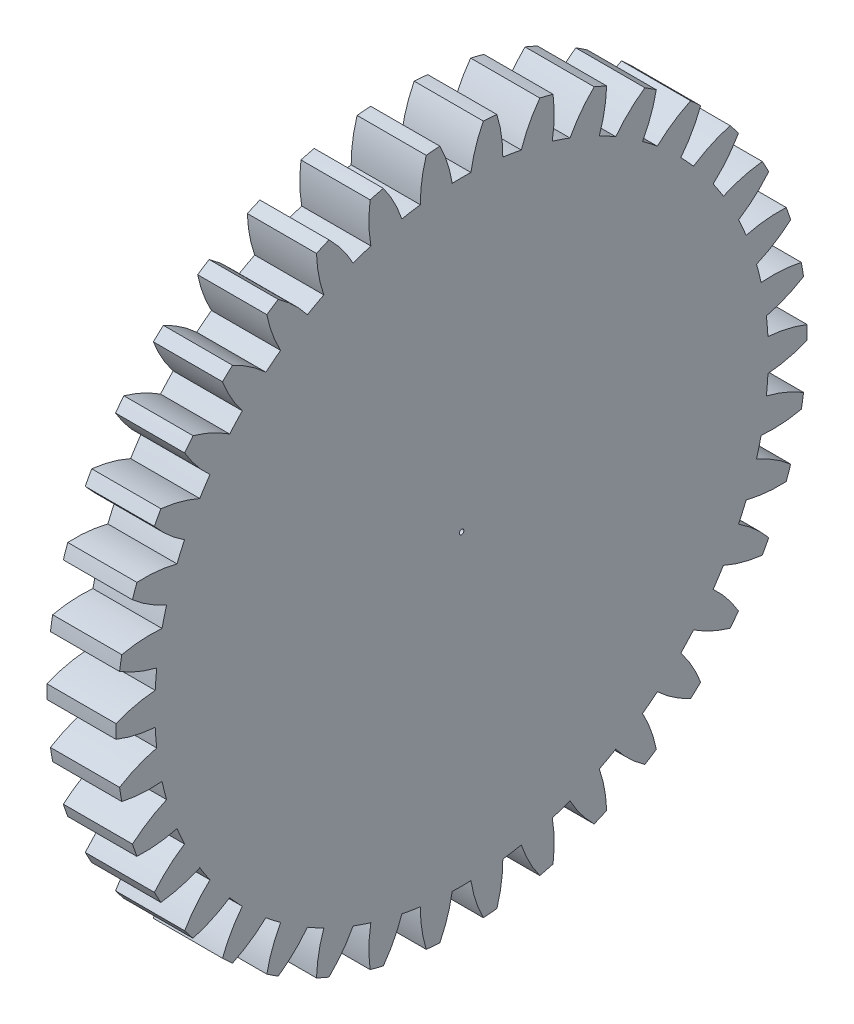
SolidWorks part; units mm, degrees
ref_plane "Plane1" through (0, 0, 0) normal (0, 0, 1) x (1, 0, 0)
ref_plane "Plane2" through (0, 0, 0) normal (0, 1, 0) x (1, 0, 0)
ref_plane "Plane3" through (0, 0, 0) normal (1, 0, 0) x (0, 0, -1)
sketch "HoldingSke" plane through (0, 0, 0) normal (0, 1, 0) x (1, 0, 0)
  line L0 (0, 0) -> (0.2627, -0.2052)
  line L1 (-15, 0) -> (100, 0) construction
  line L2 (0, 0) -> (-2.1039, 2.3779)
  line L3 (0, 0) -> (-11.863, 4.5341)
  line L4 (0, 0) -> (6.8053, 5.3169)
  line L5 (0, 0) -> (-46.8476, -17.4728)
  line L6 (0, 0) -> (-9.9476, -6.7116)
  line L7 (-2.1039, 2.3779) -> (8.6586, 51.2059)
  line L8 (-76.2, 54.61) -> (-76.1, 54.61)
  line L9 (-67.7845, 28.3722) -> (-49.3413, 33.142)
  line L10 (-76.2, 71.12) -> (104.1128, 71.12)
  line L11 (0, 0) -> (-12, 0)
  line L12 (-76.2, 101.6) -> (-76.093, 101.6)
  line L13 (24.9733, 27.94) -> (52.9518, 28.4284)
  line L14 (24.9733, 27.94) -> (24.9743, 27.94)
  line L15 (24.9733, 27.94) -> (100.4006, 29.5858)
  line L16 (-63.627, -3) -> (-12.827, -3)
  circle A0 centre (0, 0) radius 0.4
  circle A1 centre (0, 0) radius 37.5
  circle A2 centre (0, 0) radius 37.5
  circle A3 centre (0, 0) radius 0.4
  dimension "MHD" = 75
  dimension "Hub_dia" = 75
  dimension "Bore" = 0.8
  dimension "MBD" = 0.8
  dimension "Num_teeth" = 38
  dimension "Pitch_radius" = 180.3128
  dimension "Pitch" = 0.3333
  dimension "Width" = 12
  dimension "Overall_len" = 50
  dimension "Show_teeth" = 38
  dimension "Thickness" = 12
  dimension "OAL" = 50.0001
  dimension "T_dim" = 0.1
  dimension "Ap" = 14.5
  dimension "H" = 19.05
  dimension "Backlash" = 0.107
  dimension "Addendum_fac" = 1
  dimension "Dedendum_fac" = 1.25
  dimension "Clearance_fac" = 0.25
  dimension "Dedendum_add" = 0.001
  dimension "Module" = 3
sketch "BasProSke" plane through (0, 0, 0) normal (0, 1, 0) x (1, 0, 0)
  line L0 (-10, 0) -> (60, 0) construction
  line L1 (0, 0) -> (0, 60)
  line L2 (0, 0) -> (12, 0)
  line L3 (12, 0) -> (12, 60)
  line L4 (12, 60) -> (0, 60)
  dimension "Diameter" = 120
  dimension "Thickness" = 12
revolve "Base-Revolve" add sketch "BasProSke" angle 360 about L0
sketch "TooCutSke" plane through (0, 0, 0) normal (1, 0, 0) x (0, 0, -1)
  line L1 (0, 0) -> (0, 107) construction
  line L2 (0, 0) -> (-2.5427, 56.9433) construction
  line L3 (0, 0) -> (-9.4072, 113.5284) construction
  line L4 (-2.5427, 56.9433) -> (-4.7036, 56.7642) construction
  arc A0 (1.6224, 53.2243) -> (-1.6224, 53.2243) centre (0, 0) ccw
  arc A1 (3.7857, 59.9059) -> (-3.7857, 59.9059) centre (0, 0) ccw
  circle A2 centre (0, 0) radius 57 construction
  circle A3 centre (0, 0) radius 55.1844 construction
  arc A4 (-1.6224, 53.2243) -> (-3.7857, 59.9059) centre (-24.1367, 49.626) ccw
  arc A5 (3.7857, 59.9059) -> (1.6224, 53.2243) centre (24.1367, 49.626) ccw
  dimension "Root_dia" = 106.498
  dimension "Overcut_dia" = 120.0508
  dimension "Pitch_dia" = 114
  dimension "Base_dia" = 110.3688
  dimension "Flank_rad" = 22.8
  dimension "Half_ang" = 4.737
  dimension "Half_CT" = 2.1683
extrude "ToothCut" cut sketch "TooCutSke" along normal through all
fillet "Breaks" [suppressed] radius 0.06
fillet "RootFillets" [suppressed] radius 0.751
pattern_circular "TeethCuts" count 38 every 9.474 about axis through (-10, 0, 0) along (1, 0, 0) of "ToothCut", "RootFillets", "Breaks"
sketch "HubNeaOneSke" plane through (0, 0, 0) normal (-1, 0, 0) x (0, 0, 1)
  circle A0 centre (0, 0) radius 37.5
  dimension "Diameter" = 75
extrude "HubNearOne" [suppressed] add sketch "HubNeaOneSke" along normal blind 38.0001
sketch "HubNeaBotSke" plane through (0, 0, 0) normal (-1, 0, 0) x (0, 0, 1)
  circle A0 centre (0, 0) radius 37.5
  dimension "Diameter" = 75
extrude "HubNearBoth" [suppressed] add sketch "HubNeaBotSke" along normal blind 19
ref_plane "FarPln" through (12, 0, 0) normal (1, 0, 0) x (0, 0, -1)
sketch "HubFarSke" plane through (12, 0, 0) normal (1, 0, 0) x (0, 0, -1)
  circle A0 centre (0, 0) radius 37.5
  dimension "Diameter" = 75
extrude "HubFar" [suppressed] add sketch "HubFarSke" along normal blind 19
sketch "BorSke" plane through (0, 0, 0) normal (1, 0, 0) x (0, 0, -1)
  circle A0 centre (0, 0) radius 0.4
  dimension "Diameter" = 0.8
extrude "Bore" cut sketch "BorSke" along normal mid plane 100.0001
sketch "KeySke" plane through (0, 0, 0) normal (1, 0, 0) x (0, 0, -1)
  line L0 (-0.05, 0) -> (-0.05, 0.5)
  line L1 (-0.05, 0.5) -> (0.05, 0.5)
  line L2 (0.05, 0.5) -> (0.05, 0)
  line L3 (0, 0) -> (0, 34) construction
  line L4 (-0.05, 0) -> (0.05, 0)
  dimension "Offset" = 0.5
  dimension "Width" = 0.1
extrude "Keyway" [suppressed] cut sketch "KeySke" along normal mid plane 100.0001
pattern_circular "Keyway2" [suppressed] count 2 every 90 about axis through (-10, 0, 0) along (1, 0, 0)
equation "' \"Module@HoldingSke\" = 6.35"
equation "' \"Num_teeth@HoldingSke\" = 12"
equation "' \"Ap@HoldingSke\" =  20"
equation "' \"Width@HoldingSke\" = 0.5 * 25.4"
equation "' \"Hub_dia@HoldingSke\"= 1 * 25.4"
equation "' \"Overall_len@HoldingSke\" = 1.0 * 25.4"
equation "' \"Bore@HoldingSke\" = 0.75 * 25.4"
equation "' \"T_dim@HoldingSke\" = 0.1 * 25.4"
equation "' \"Width@KeySke\" = 0.25 * 25.4"
equation "' \"Show_teeth@HoldingSke\" = 13"
equation "' \"Backlash@HoldingSke\" = 0.009 * 25.4"
equation "' \"Addendum_fac@HoldingSke\" = 1.0"
equation "' \"Dedendum_fac@HoldingSke\" = 1.25"
equation "' \"Dedendum_add@HoldingSke\" = 0.00005 * 25.4"
equation "' \"Clearance_fac@HoldingSke\" = 0.25"
equation "\"Pitch@HoldingSke\" = 1 / \"Module@HoldingSke\""
equation "\"Overcut_dia@TooCutSke\" = (\"Num_teeth@HoldingSke\" + 2 * \"Addendum_fac@HoldingSke\") / \"Pitch@HoldingSke\" + 0.002 * 25.4"
equation "\"Pitch_dia@TooCutSke\" = \"Num_teeth@HoldingSke\" / \"Pitch@HoldingSke\""
equation "\"Base_dia@TooCutSke\" = \"Num_teeth@HoldingSke\" / \"Pitch@HoldingSke\" * cos((\"Ap@HoldingSke\"  * 3.14159265 / 180))"
equation "\"Root_dia@TooCutSke\" = (\"Num_teeth@HoldingSke\" + 2) / \"Pitch@HoldingSke\" - 2 * (\"Addendum_fac@HoldingSke\" + \"Dedendum_fac@HoldingSke\") / \"Pitch@HoldingSke\" - \"Dedendum_add@HoldingSke\" * 2"
equation "\"Half_ang@TooCutSke\" = 180 / \"Num_teeth@HoldingSke\""
equation "\"Half_CT@TooCutSke\" = \"Num_teeth@HoldingSke\" / \"Pitch@HoldingSke\" * sin((3.14159265 / 2 / \"Num_teeth@HoldingSke\")) / 2 - 7 * \"Backlash@HoldingSke\" / 4"
equation "\"Flank_rad@TooCutSke\" = \"Num_teeth@HoldingSke\" / \"Pitch@HoldingSke\" / 5"
equation "\"Radius@RootFillets\" = \"Clearance_fac@HoldingSke\" / \"Pitch@HoldingSke\" + \"Dedendum_add@HoldingSke\""
equation "\"Break_rad@Breaks\" = 0.02 / \"Pitch@HoldingSke\""
equation "\"Thickness@HoldingSke\" = \"Width@HoldingSke\""
equation "\"OAL@HoldingSke\" = \"Thickness@HoldingSke\""
equation "\"MHD@HoldingSke\" = (\"Num_teeth@HoldingSke\" + 2) / \"Pitch@HoldingSke\" - 2 * (\"Addendum_fac@HoldingSke\" + \"Dedendum_fac@HoldingSke\")  / \"Pitch@HoldingSke\" - \"Dedendum_add@HoldingSke\" * 2"
equation "\"MBD@HoldingSke\" = (\"Num_teeth@HoldingSke\" + 2) / \"Pitch@HoldingSke\" - 2 * (\"Addendum_fac@HoldingSke\" + \"Dedendum_fac@HoldingSke\")  / \"Pitch@HoldingSke\" - \"Dedendum_add@HoldingSke\" * 2 - 0.002 * 25.4"
equation "\"MHD@HoldingSke\" = ((sgn( \"MHD@HoldingSke\" - \"Hub_dia@HoldingSke\" )-1)*( \"MHD@HoldingSke\" - \"Hub_dia@HoldingSke\" ))/-2+ \"Hub_dia@HoldingSke\""
equation "\"MBD@HoldingSke\" = ((sgn( \"MBD@HoldingSke\" - \"Bore@HoldingSke\" )-1)*( \"MBD@HoldingSke\" - \"Bore@HoldingSke\" ))/-2+ \"Bore@HoldingSke\""
equation "\"OAL@HoldingSke\" = ((sgn( \"OAL@HoldingSke\" - \"Overall_len@HoldingSke\" )+1)*( \"OAL@HoldingSke\" - \"Overall_len@HoldingSke\" ))/2 + \"Overall_len@HoldingSke\" + 0.000002 * 25.4"
equation "\"Num_teeth@TeethCuts\" = int( \"Show_teeth@HoldingSke\" ) + 1"
equation "\"Num_teeth@TeethCuts\" = ((sgn( \"Num_teeth@TeethCuts\" - \"Num_teeth@HoldingSke\" )-1)*( \"Num_teeth@TeethCuts\" - \"Num_teeth@HoldingSke\" ))/-2+ \"Num_teeth@HoldingSke\""
equation "\"Num_teeth@TeethCuts\" = ((sgn( \"Num_teeth@TeethCuts\" - 2.0)+1)*( \"Num_teeth@TeethCuts\" - 2.0))/2 +2.0"
equation "\"Angle@TeethCuts\" = 360.0 / \"Num_teeth@HoldingSke\""
equation "\"Diameter@BasProSke\" = (\"Num_teeth@HoldingSke\" + 2 * \"Addendum_fac@HoldingSke\") / \"Pitch@HoldingSke\""
equation "\"Thickness@BasProSke\"  = \"Thickness@HoldingSke\""
equation "' \"Fillet_rad@BasProSke\" =  \"Thickness@HoldingSke\" * 0.05"
equation "\"MHD@HoldingSke\" = ((sgn( \"MHD@HoldingSke\" - \"Root_dia@TooCutSke\" )-1)*( \"MHD@HoldingSke\" - \"Root_dia@TooCutSke\" ))/-2+ \"Root_dia@TooCutSke\""
equation "\"Diameter@HubNeaOneSke\" = \"MHD@HoldingSke\""
equation "\"Length@HubNearOne\" = \"OAL@HoldingSke\" - \"Thickness@BasProSke\""
equation "\"Diameter@HubNeaBotSke\" = \"MHD@HoldingSke\""
equation "\"Length@HubNearBoth\" = ( \"OAL@HoldingSke\" - \"Thickness@BasProSke\" ) / 2.0"
equation "\"Thickness@FarPln\" = \"Thickness@BasProSke\""
equation "\"Diameter@HubFarSke\" = \"MHD@HoldingSke\""
equation "\"Length@HubFar\" = ( \"OAL@HoldingSke\" - \"Thickness@BasProSke\" ) / 2.0"
equation "\"Diameter@BorSke\" = \"MBD@HoldingSke\""
equation "\"D1@Bore\" = \"OAL@HoldingSke\" * 2.0"
equation "\"D1@Keyway\" = \"OAL@HoldingSke\" * 2.0"
equation "\"Offset@KeySke\" = \"T_dim@HoldingSke\" + \"MBD@HoldingSke\" / 2.0"
